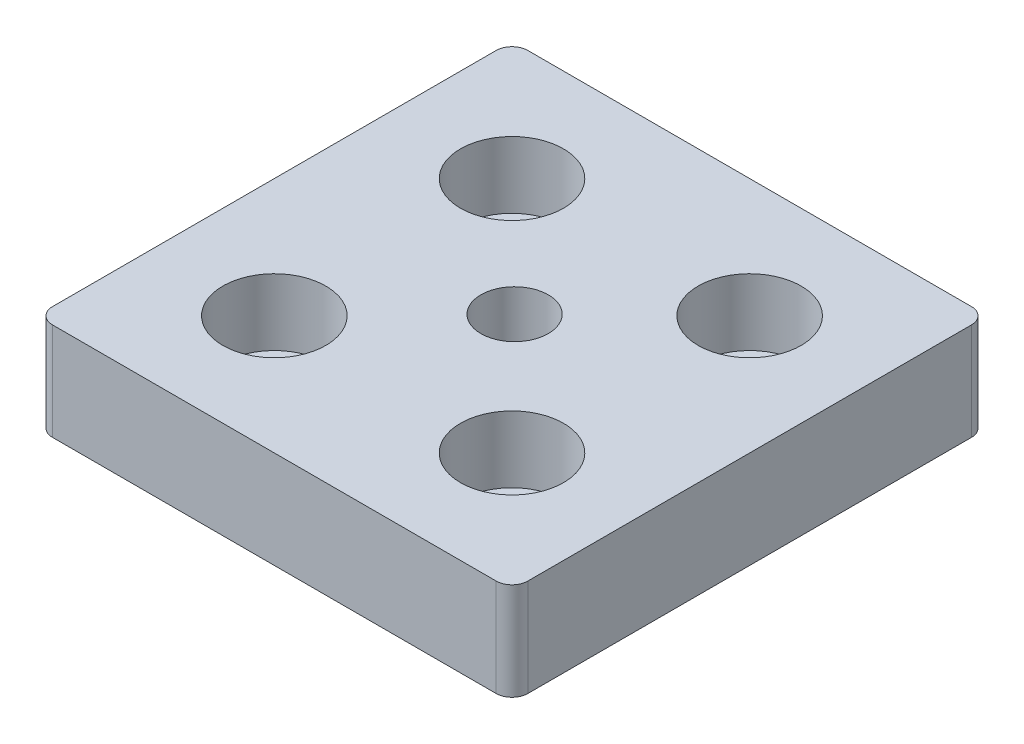
SolidWorks part; units mm, degrees
ref_plane "前视基准面" through (0, 0, 0) normal (0, 0, 1) x (1, 0, 0)
ref_plane "上视基准面" through (0, 0, 0) normal (0, 1, 0) x (1, 0, 0)
ref_plane "右视基准面" through (0, 0, 0) normal (1, 0, 0) x (0, 0, -1)
sketch "草图1" plane through (0, 0, 0) normal (0, 1, 0) x (1, 0, 0)
  line B0 (-27.9936, -30.3305) -> (28.0064, -30.3305)
  line B1 (30.0064, -28.3305) -> (30.0064, 27.6695)
  line B2 (28.0064, 29.6695) -> (-27.9936, 29.6695)
  line B3 (-29.9936, 27.6695) -> (-29.9936, -28.3305)
  arc B4 (28.0064, -30.3305) -> (30.0064, -28.3305) centre (28.0064, -28.3305) ccw
  arc B5 (30.0064, 27.6695) -> (28.0064, 29.6695) centre (28.0064, 27.6695) ccw
  arc B6 (-27.9936, 29.6695) -> (-29.9936, 27.6695) centre (-27.9936, 27.6695) ccw
  arc B7 (-29.9936, -28.3305) -> (-27.9936, -30.3305) centre (-27.9936, -28.3305) ccw
  circle B8 centre (15.0064, -15.3305) radius 4.5
  circle B9 centre (15.0064, 14.6695) radius 4.5
  circle B10 centre (-14.9936, 14.6695) radius 4.5
  circle B11 centre (-14.9936, -15.3305) radius 4.5
sketch_block_instance "A$C3E071CC2-1"
sketch_block "A$C3E071CC2"
extrude "凸台-拉伸1" add sketch "草图1" along normal blind 12.3
sketch "草图3" plane through (0, 12.3, 0) normal (0, 1, 0) x (1, 0, 0)
  point P4 (0, 0)
hole_wizard "M10 螺纹孔1" positions "3D草图1" profile "草图4" tap size "M10" standard "Iso"
sketch3d "3D草图1"
  point P0 (0, 12.3, 0)
sketch "草图4" plane through (0, 12.3, 0) normal (1, 0, 0) x (0, 0, 1)
  line L0 (0, 0) -> (0, 27.0537)
  line L1 (0, 27.0537) -> (4.25, 24.5)
  line L2 (4.25, 24.5) -> (4.25, 0)
  line L5 (4.25, 0) -> (0, 0)
  line L10 (0, 27.0537) -> (-4.25, 24.5) construction
  line L11 (0, -6.35) -> (0, 107.95) construction
  dimension "螺纹孔钻头直径" = 8.5
  dimension "螺纹孔钻头深度" = 24.5
  dimension "导头角度" = 118
cosmetic thread "孔螺蚊线1" parameters "D1"=12.3, "D2"=10
sketch "草图5" plane through (0, 12.3, 0) normal (0, 1, 0) x (1, 0, 0)
  circle A0 centre (-14.9936, 14.6695) radius 6.5
  circle A1 centre (15.0064, 14.6695) radius 6.5
  circle A2 centre (15.0064, -15.3305) radius 6.5
  circle A3 centre (-14.9936, -15.3305) radius 6.5
extrude "切除-拉伸1" cut sketch "草图5" against normal blind 8.4
